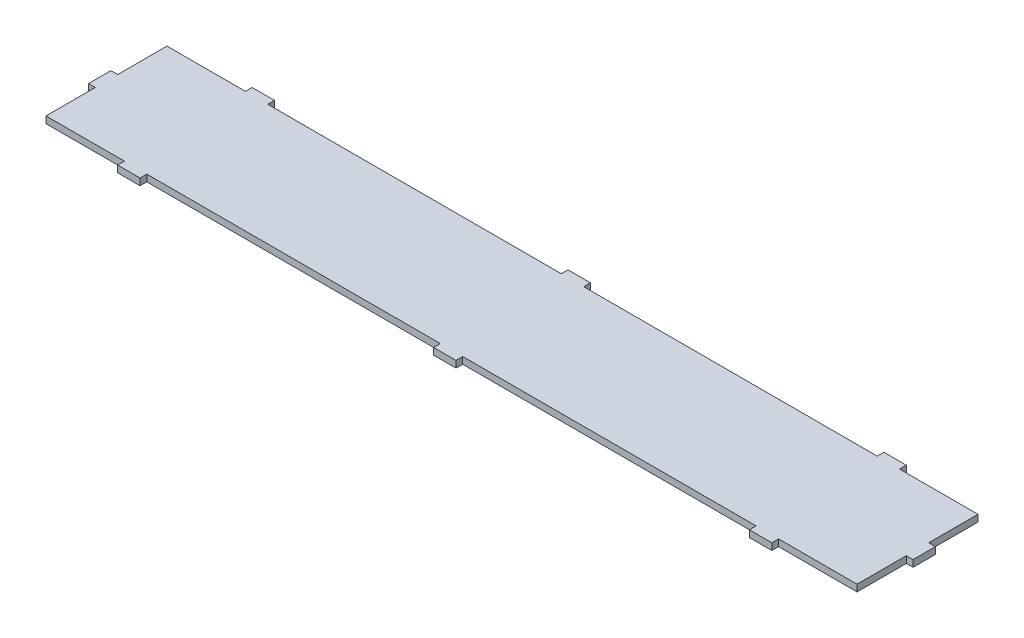
SolidWorks part; units mm, degrees
ref_plane "Front Plane" through (0, 0, 0) normal (0, 0, 1) x (1, 0, 0)
ref_plane "Top Plane" through (0, 0, 0) normal (0, 1, 0) x (1, 0, 0)
ref_plane "Right Plane" through (0, 0, 0) normal (1, 0, 0) x (0, 0, -1)
sketch "Sketch1" plane through (0, 0, 0) normal (0, 1, 0) x (1, 0, 0)
  line L0 (-181, 27) -> (-181, 5)
  line L1 (146, 30) -> (136, 30)
  line L3 (146, -30) -> (136, -30)
  line L4 (-184, 5) -> (-184, -5)
  line L7 (-181, 5) -> (-184, 5)
  line L8 (-181, -5) -> (-184, -5)
  line L9 (-181, -5) -> (-181, -27)
  line L10 (184, 5) -> (181, 5)
  line L11 (184, -5) -> (181, -5)
  line L12 (-146, 30) -> (-146, 27)
  line L13 (-136, 27) -> (-5, 27)
  line L14 (-136, 27) -> (-136, 30)
  line L15 (146, 30) -> (146, 27)
  line L16 (146, 27) -> (181, 27)
  line L17 (136, 27) -> (136, 30)
  line L18 (5, 27) -> (136, 27)
  line L19 (5, 27) -> (5, 30)
  line L20 (-5, 27) -> (-5, 30)
  line L21 (-181, 27) -> (-146, 27)
  line L22 (5, 30) -> (-5, 30)
  line L23 (-136, 30) -> (-146, 30)
  line L24 (184, 5) -> (184, -5)
  line L25 (136, -27) -> (136, -30)
  line L26 (146, -30) -> (146, -27)
  line L27 (146, -30) -> (136, -30)
  line L28 (5, -30) -> (-5, -30)
  line L29 (-5, -27) -> (-5, -30)
  line L30 (5, -27) -> (5, -30)
  line L31 (-136, -30) -> (-146, -30)
  line L32 (-136, -27) -> (-136, -30)
  line L33 (-146, -30) -> (-146, -27)
  line L34 (-181, -27) -> (-146, -27)
  line L35 (-136, -27) -> (-5, -27)
  line L36 (-136, -30) -> (-146, -30)
  line L37 (5, -27) -> (136, -27)
  line L38 (5, -30) -> (-5, -30)
  line L39 (146, -27) -> (181, -27)
  line L40 (181, 5) -> (181, 27)
  line L41 (181, -5) -> (181, -27)
  point P0 (0, 0)
  point P8 (0, 0)
  point P14 (0, -30)
  point P16 (0, 30)
  dimension "D1" = 3
  dimension "D2" = 35
  dimension "D3" = 10
  dimension "D4" = 10
  dimension "D5" = 368
  dimension "D6" = 10
  dimension "D7" = 3
  dimension "D8" = 60
  dimension "D9" = 10
  dimension "D10" = 10
  dimension "D11" = 35
  dimension "D12" = 3
  dimension "D13" = 10
  dimension "D14" = 10
  dimension "D15" = 3
  dimension "D16" = 35
  dimension "D17" = 3
  dimension "D18" = 3
  dimension "D19" = 3
  dimension "D20" = 3
  dimension "D21" = 35
  dimension "D22" = 10
  dimension "D23" = 3
  dimension "D24" = 131
  dimension "D25" = 131
  dimension "D26" = 131
  dimension "D27" = 131
extrude "Boss-Extrude1" add sketch "Sketch1" along normal blind 3
